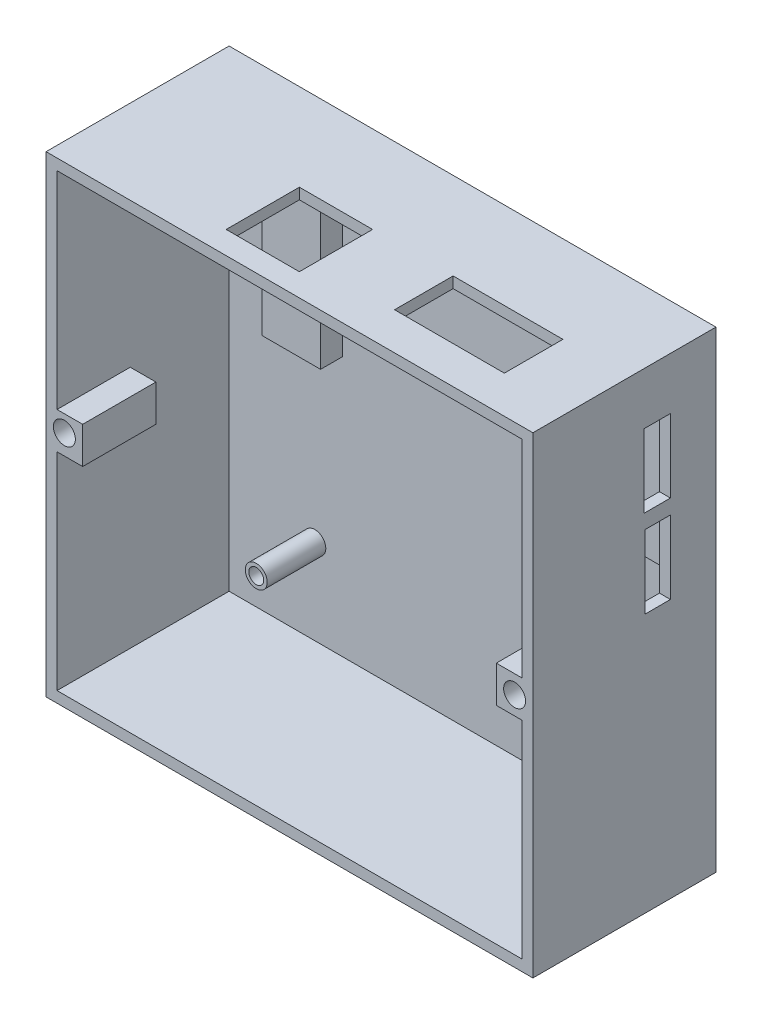
SolidWorks part; units mm, degrees
ref_plane "Front Plane" through (0, 0, 0) normal (0, 0, 1) x (1, 0, 0)
ref_plane "Top Plane" through (0, 0, 0) normal (0, 1, 0) x (1, 0, 0)
ref_plane "Right Plane" through (0, 0, 0) normal (1, 0, 0) x (0, 0, -1)
sketch "Sketch1" plane through (0, 0, 0) normal (0, 0, 1) x (1, 0, 0)
  line L1 (-33.25, 32.25) -> (33.25, 32.25)
  line L2 (-33.25, 32.25) -> (-33.25, -32.25)
  line L3 (-33.25, -32.25) -> (33.25, -32.25)
  line L4 (33.25, 32.25) -> (33.25, -32.25)
  line L5 (-33.25, 32.25) -> (33.25, -32.25) construction
  line L6 (-33.25, -32.25) -> (33.25, 32.25) construction
  point P0 (0, 0)
  dimension "D1" = 64.5
  dimension "D2" = 66.5
extrude "Boss-Extrude1" add sketch "Sketch1" along normal blind 25
sketch "Sketch2" plane through (0, 0, 25) normal (0, 0, 1) x (1, 0, 0)
  line L0 (0, 32.25) -> (0, -38.2518) construction
  line L1 (33.25, 32.25) -> (-33.25, 32.25) construction
  line L2 (-33.25, 0) -> (36.5808, 0) construction
  line L3 (-33.25, 32.25) -> (-33.25, -32.25) construction
  line L5 (-31.75, 30.75) -> (31.75, 30.75)
  line L6 (-31.75, 30.75) -> (-31.75, -30.75)
  line L7 (-31.75, -30.75) -> (31.75, -30.75)
  line L8 (31.75, 30.75) -> (31.75, -30.75)
  line L9 (-31.75, 30.75) -> (31.75, -30.75) construction
  line L10 (-31.75, -30.75) -> (31.75, 30.75) construction
  point P9 (0, 0)
  dimension "D1" = 61.5
  dimension "D2" = 63.5
extrude "Cut-Extrude2" cut sketch "Sketch2" against normal blind 23.5
sketch "Sketch6" plane through (-33.25, 0, 0) normal (-1, 0, 0) x (0, 0, 1)
  line L3 (12.8894, 8.7451) -> (14.3249, 8.7451) construction
sketch "Sketch9" plane through (-33.25, 0, 0) normal (-1, 0, 0) x (0, 0, 1)
  line L0 (12.5, 32.25) -> (12.5, -32.25) construction
  line L1 (25, 32.25) -> (0, 32.25) construction
  line L2 (25, -32.25) -> (0, -32.25) construction
  line L3 (0, 0) -> (25, 0) construction
  line L4 (25, 32.25) -> (25, -32.25) construction
  line L6 (15, 2.5) -> (25, 2.5)
  line L7 (15, 2.5) -> (15, -2.5)
  line L8 (15, -2.5) -> (25, -2.5)
  line L9 (25, 2.5) -> (25, -2.5)
  line L10 (15, 2.5) -> (25, -2.5) construction
  line L11 (15, -2.5) -> (25, 2.5) construction
  point P11 (20, 0)
  dimension "D1" = 10
  dimension "D2" = 5
extrude "Boss-Extrude5" add sketch "Sketch9" against normal blind 5
sketch "Sketch14" plane through (0, 0, 25) normal (0, 0, 1) x (1, 0, 0)
  line L0 (-28.25, 0.2282) -> (-33.25, 0.2282) construction
  line L1 (-28.25, -2.5) -> (-28.25, 2.5) construction
  line L2 (-33.25, 32.25) -> (-33.25, -32.25) construction
  line L3 (-30.75, 0.2282) -> (-30.75, 3.8977) construction
  line L4 (-30.75, 0.2282) -> (-30.75, -2.9959) construction
  circle A0 centre (-30.75, 0.2282) radius 1.5
  dimension "D1" = 3
extrude "Cut-Extrude4" cut sketch "Sketch14" against normal blind 9
sketch "Sketch17" plane through (33.25, 0, 0) normal (1, 0, 0) x (0, 0, -1)
  line L0 (-12.5, 32.25) -> (-11.914, -33.4224) construction
  line L1 (-25, 32.25) -> (0, 32.25) construction
  line L2 (0, 0) -> (-25, 0) construction
  line L3 (-25, -32.25) -> (-25, 32.25) construction
  line L4 (0, 0) -> (-25, 0)
  line L6 (-25, 2.5) -> (-15, 2.5)
  line L7 (-25, 2.5) -> (-25, -2.5)
  line L8 (-25, -2.5) -> (-15, -2.5)
  line L9 (-15, 2.5) -> (-15, -2.5)
  line M7 (-25, 32.25) -> (-25, -32.25)
  dimension "D1" = 2.5
  dimension "D2" = 2.5
  dimension "D3" = 10
  dimension "D4" = 0
extrude "Boss-Extrude7" add sketch "Sketch17" against normal blind 5 contours L9 L6 L4 M7 | L9 L4 L8 M7
sketch "Sketch18" plane through (0, 0, 25) normal (0, 0, 1) x (1, 0, 0)
  line L0 (28.25, 0) -> (33.25, 0) construction
  line L1 (28.25, 2.5) -> (28.25, -2.5) construction
  line L2 (33.25, -32.25) -> (33.25, 32.25) construction
  line L3 (30.75, 0) -> (30.75, 3.3646) construction
  circle A0 centre (30.75, 0) radius 1.5
  dimension "D1" = 3
extrude "Cut-Extrude6" cut sketch "Sketch18" against normal blind 9
sketch "Sketch19" plane through (0, 0, 1.5) normal (0, 0, 1) x (1, 0, 0)
  circle A1 centre (-20.04, 29.09) radius 1.5
  circle A2 centre (30.04, 29.09) radius 1.5
  circle A3 centre (-20.04, -19.09) radius 1.5
  circle A4 centre (30.04, -18.96) radius 1.5
  point P23 (31.54, -18.9392)
  point P24 (31.54, -18.9837)
  dimension "D5" = 3
extrude "Boss-Extrude9" add sketch "Sketch19" along normal blind 8
sketch "Sketch22" plane through (0, 0, 9.5) normal (0, 0, 1) x (1, 0, 0)
  line L0 (-20.04, 30.59) -> (-20.04, 27.59) construction
  line L1 (-21.54, 29.09) -> (-18.54, 29.09) construction
  line L2 (30.04, 30.59) -> (30.04, 27.5082) construction
  line L3 (28.54, 29.09) -> (31.54, 29.09) construction
  line L4 (30.04, -17.46) -> (30.04, -20.46) construction
  line L5 (28.54, -18.96) -> (31.54, -18.96) construction
  line L6 (-20.04, -17.59) -> (-20.04, -21.3411) construction
  line L7 (-21.54, -19.09) -> (-18.54, -19.09) construction
  circle A0 centre (-20.04, 29.09) radius 1.5 construction
  circle A1 centre (-20.04, 29.09) radius 1.5 construction
  circle A2 centre (-20.04, 29.09) radius 1.015
  circle A5 centre (30.04, 29.09) radius 1.5 construction
  circle A6 centre (30.04, 29.09) radius 1.5 construction
  circle A7 centre (30.04, 29.0491) radius 1.015
  circle A8 centre (30.04, -18.96) radius 1.5 construction
  circle A9 centre (30.04, -18.96) radius 1.5 construction
  circle A10 centre (30.04, -18.96) radius 1.015
  circle A11 centre (-20.04, -19.09) radius 1.5 construction
  circle A12 centre (-20.04, -19.09) radius 1.5 construction
  circle A13 centre (-20.04, -19.09) radius 1.015
  dimension "D1" = 2.03
  dimension "D2" = 2.03
  dimension "D3" = 2.03
  dimension "D4" = 2.03
extrude "Cut-Extrude7" cut sketch "Sketch22" against normal blind 7.5
sketch "Sketch23" plane through (0, 0, 1.5) normal (0, 0, 1) x (1, 0, 0)
  line L0 (31.75, -30.75) -> (31.75, 30.75) construction
  line L1 (31.75, 24.75) -> (-24.25, 24.75)
  line L2 (31.75, 24.75) -> (31.75, 4.75)
  line L3 (31.75, 4.75) -> (-24.25, 4.75)
  line L4 (-24.25, 24.75) -> (-24.25, 4.75)
  line L5 (31.75, 30.75) -> (-31.75, 30.75) construction
  point P10 (62.6172, 15.2745)
  dimension "D1" = 56
  dimension "D2" = 20
  dimension "D3" = 6
extrude "Boss-Extrude12" add sketch "Sketch23" along normal blind 3
sketch "Sketch26" plane through (0, 0, 4.5) normal (0, 0, 1) x (1, 0, 0)
  line L0 (31.75, 24.75) -> (-24.25, 24.75) construction
  line L1 (-16.25, 24.75) -> (25.75, 24.75)
  line L2 (-16.25, 24.75) -> (-16.25, 4.75)
  line L3 (-16.25, 4.75) -> (25.75, 4.75)
  line L4 (25.75, 24.75) -> (25.75, 4.75)
  line L5 (-24.25, 4.75) -> (31.75, 4.75) construction
  line L6 (31.75, 4.75) -> (31.75, 24.75) construction
  dimension "6" = 6
  dimension "D2" = 42
extrude "Cut-Extrude9" cut sketch "Sketch26" against normal blind 3
sketch "Sketch27" plane through (31.75, 0, 0) normal (-1, 0, 0) x (0, 0, 1)
  line L0 (0, 14.1355) -> (25, 14.1355) construction
  line L1 (0, 32.25) -> (0, -32.25) construction
  line L2 (25, 32.25) -> (25, -32.25) construction
sketch "Sketch38" plane through (31.75, 0, 0) normal (-1, 0, 0) x (0, 0, 1)
  line L0 (0, 14.1355) -> (25, 14.1355)
sketch "Sketch39" plane through (31.75, 0, 0) normal (-1, 0, 0) x (0, 0, 1)
  line L0 (1.551, 24.7359) -> (25, 24.7359)
  line L1 (25, 32.25) -> (25, -32.25) construction
  line L2 (1.551, 24.7359) -> (0, 24.7359)
  line L3 (0, 32.25) -> (0, -32.25) construction
  line L4 (0, 14.1355) -> (25, 14.1355) construction
  dimension "D1" = 10.6003
sketch "Sketch40" plane through (31.75, 0, 0) normal (-1, 0, 0) x (0, 0, 1)
  line L0 (0, 4.9226) -> (25, 4.9226)
  line L1 (0, 32.25) -> (0, -32.25) construction
  line L2 (25, 32.25) -> (25, -32.25) construction
sketch "Sketch41" plane through (31.75, 0, 0) normal (-1, 0, 0) x (0, 0, 1)
  line L0 (4.6148, 24.7359) -> (4.6148, 3.7484)
  line L1 (1.551, 24.7359) -> (25, 24.7359) construction
sketch "Sketch45" plane through (33.25, 0, 0) normal (1, 0, 0) x (0, 0, -1)
  line L3 (-6.2148, 15.1355) -> (-6.2148, 24.7359)
  line L4 (-1.551, 24.7359) -> (-25, 24.7359) construction
  line L5 (-6.2148, 13.1355) -> (-6.2148, 4.4365)
  line L6 (-6.2148, 15.1355) -> (-6.2148, 25.1355)
  line L7 (-6.2148, 25.1355) -> (-9.8148, 25.1355)
  line L8 (-9.8148, 25.1355) -> (-9.8148, 15.1355)
  line L10 (-9.7148, 13.1355) -> (-9.7148, 3.1355)
  line L11 (-9.7148, 3.1355) -> (-6.2148, 3.1355)
  line L12 (-6.2148, 3.1355) -> (-6.2148, 13.1355)
  line L14 (-9.7148, 13.1355) -> (-6.2148, 13.1355)
  line L15 (-9.8148, 15.1355) -> (-6.2148, 15.1355)
  point P0 (0, 0)
  dimension "D1" = 10
  dimension "D2" = 10
  dimension "D3" = 3.6
extrude "Cut-Extrude12" cut sketch "Sketch45" against normal blind 3 contours L8 L15 L3 L6 L7 | L14 L10 L11 L12 L5
sketch "Sketch46" plane through (0, 32.25, 0) normal (0, 1, 0) x (1, 0, 0)
  line L0 (-21.75, -11.9) -> (-11.75, -11.9)
  line L1 (33.25, 0) -> (-33.25, 0) construction
  line L4 (-21.75, -11.9) -> (31.75, -11.9)
  line L6 (31.75, 0) -> (31.75, -25) construction
  line L7 (-11.2631, -11.9) -> (-11.75, -11.9)
  line L8 (31.75, 0) -> (31.75, -26.7121)
  line L9 (33.25, -25) -> (33.25, 0) construction
  line L10 (31.75, -11.9) -> (-11.75, -11.9)
  line L11 (31.75, -11.9) -> (-21.75, -11.9)
  line L12 (-21.75, -11.9) -> (31.75, -11.9)
  line L13 (-21.75, -11.9) -> (-21.75, 0)
  line L14 (-11.75, -11.9) -> (-11.75, -21.9)
  line L15 (-11.75, -21.9) -> (-1.75, -21.9)
  line L16 (-1.75, -21.9) -> (-1.75, -11.9)
  dimension "D1" = 10
  dimension "D2" = 10
  dimension "D3" = 1.5
  dimension "D4" = 53.5
  dimension "D5" = 10
  dimension "D6" = 10
extrude "Cut-Extrude13" cut sketch "Sketch46" against normal blind 3 contours L15 L16 L4 L14
sketch "Sketch47" plane through (0, 0, 25) normal (0, 0, 1) x (1, 0, 0)
  line L2 (-28.25, 2.5) -> (-31.75, 2.5) construction
  line L3 (-31.4191, 2.5) -> (-28.25, 2.5)
sketch "Sketch48" plane through (0, 0, 1.5) normal (0, 0, 1) x (1, 0, 0)
  line L0 (-31.4861, -2.5) -> (-30.9326, -2.5)
  line L5 (-28.25, -2.5) -> (-31.75, -2.5) construction
  line L6 (-33.25, -32.25) -> (33.25, -32.25) construction
  dimension "D1" = 29.75
sketch "Sketch49" plane through (0, 0, 16) normal (0, 0, 1) x (1, 0, 0)
  line L0 (-29.25, 0.2282) -> (-29.25, 2.7962)
  line L1 (-30.75, 1.7282) -> (-27.7603, 1.7282)
  line L2 (-28.25, -2.5) -> (-28.25, 2.5) construction
  line L3 (-31.4191, 2.5) -> (-28.25, 2.5) construction
  circle A0 centre (-30.75, 0.2282) radius 1.5 construction
  circle A1 centre (-30.75, 0.2282) radius 1.5 construction
  point P13 (0, 0)
  dimension "D1" = 1
  dimension "D2" = 0.7718
sketch "Sketch50" plane through (0, 0, 25) normal (0, 0, 1) x (1, 0, 0)
  line L0 (-30.75, 1.7282) -> (-30.75, -1.2718) construction
  line L1 (-32.25, 0.2282) -> (-29.25, 0.2282) construction
  line L2 (33.25, 32.25) -> (-33.25, 32.25) construction
  line L7 (-33.25, -32.25) -> (33.25, -32.25) construction
  line L8 (-33.25, 32.25) -> (-33.25, -32.25) construction
  line L9 (30.75, 1.5) -> (30.75, -1.5) construction
  line L10 (29.25, 0) -> (32.25, 0) construction
  line L15 (33.25, -32.25) -> (33.25, 32.25) construction
  circle A0 centre (-30.75, 0.2282) radius 1.5 construction
  circle A1 centre (-30.75, 0.2282) radius 1.5 construction
  circle A2 centre (30.75, 0) radius 1.5 construction
  circle A3 centre (30.75, 0) radius 1.5 construction
  point P12 (-30.75, 0.2282)
  point P23 (30.75, 0)
  point P29 (56.4546, -6.9457)
  dimension "D1" = 64.5
  dimension "D2" = 32.4782
  dimension "D3" = 32.0218
  dimension "D4" = 2.5
  dimension "D5" = 32.25
  dimension "D6" = 32.25
  dimension "D7" = 2.5
sketch "Sketch51" plane through (0, 32.25, 0) normal (0, 1, 0) x (1, 0, 0)
  line L0 (9.25, -11.9) -> (24.25, -11.9)
  line L1 (-11.75, -11.9) -> (-34.1087, -11.9)
  line L4 (24.25, -11.9) -> (24.25, -19.9)
  line L5 (24.25, -19.9) -> (9.25, -19.9)
  line L6 (9.25, -19.9) -> (9.25, -11.9)
  dimension "D2" = 8
  dimension "D3" = 15
extrude "Cut-Extrude14" cut sketch "Sketch51" against normal blind 1.5 contours L6 L5 L4 L0
